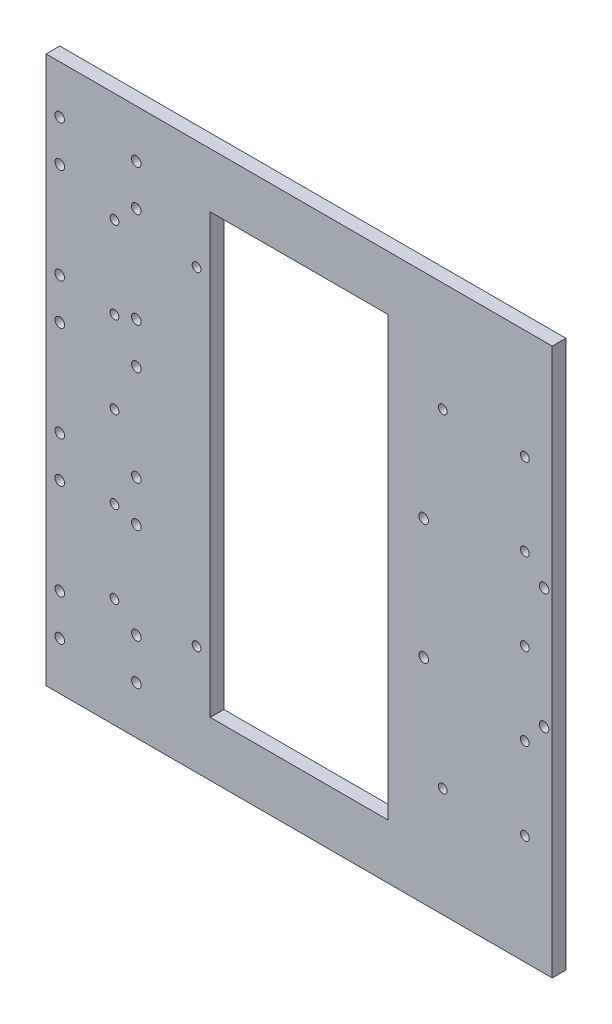
SolidWorks part; units mm, degrees
ref_plane "前视基准面" through (0, 0, 0) normal (0, 0, 1) x (1, 0, 0)
ref_plane "上视基准面" through (0, 0, 0) normal (0, 1, 0) x (1, 0, 0)
ref_plane "右视基准面" through (0, 0, 0) normal (1, 0, 0) x (0, 0, -1)
other "Configuration Table"
sketch "草图1" plane through (0, 0, 0) normal (0, 0, 1) x (1, 0, 0)
  line L1 (0, 0) -> (170, 0)
  line L2 (0, 0) -> (0, 140)
  line L3 (0, 140) -> (170, 140)
  line L4 (170, 0) -> (170, 140)
  dimension "D1" = 170
  dimension "D2" = 140
extrude "凸台-拉伸1" add sketch "草图1" along normal blind 5
sketch "草图3" plane through (0, 0, 5) normal (0, 0, 1) x (1, 0, 0)
  line L0 (160, 130) -> (10, 130)
  line L1 (10, 130) -> (10, 10)
  line L2 (10, 10) -> (160, 10)
  line L3 (160, 10) -> (160, 130)
  line L4 (0, 140) -> (0, 0)
  line L5 (0, 0) -> (170, 0)
  line L6 (170, 0) -> (170, 140)
  line L7 (170, 140) -> (0, 140)
  line L8 (0, 140) -> (0, 0)
  line L9 (0, 0) -> (170, 0)
  line L10 (170, 0) -> (170, 140)
  line L11 (170, 140) -> (0, 140)
  circle A0 centre (10, 130) radius 1.6
  circle A1 centre (160, 130) radius 1.6
  circle A2 centre (10, 10) radius 1.6
  circle A3 centre (160, 10) radius 1.6
  dimension "D3" = 3.2
  dimension "D4" = 3.2
  dimension "D5" = 3.2
  dimension "D6" = 3.2
  dimension "D1" = 0
  dimension "D2" = 10
extrude "切除-拉伸1" cut sketch "草图3" against normal blind 5 contours L0 A0 L1 | L1 A0 L0 | L1 A2 L2 | L2 A2 L1 | L3 A3 L2 | L2 A3 L3 | L0 A1 L3 | L3 A1 L0
sketch "草图4" plane through (0, 0, 5) normal (0, 0, 1) x (1, 0, 0)
  circle A0 centre (10, 130) radius 1.6 construction
  circle A1 centre (10, 130) radius 1.6
  circle A2 centre (40, 130) radius 1.6
  circle A3 centre (70, 130) radius 1.6
  circle A4 centre (100, 130) radius 1.6
  circle A5 centre (130, 130) radius 1.6
  circle A6 centre (160, 130) radius 1.6 construction
  circle A7 centre (10, 10) radius 1.6 construction
  circle A8 centre (10, 10) radius 1.6
  circle A9 centre (40, 10) radius 1.6
  circle A10 centre (70, 10) radius 1.6
  circle A11 centre (100, 10) radius 1.6
  circle A12 centre (130, 10) radius 1.6
  circle A13 centre (160, 10) radius 1.6 construction
  circle A14 centre (160, 130) radius 1.6
  circle A15 centre (10, 100) radius 1.6
  circle A16 centre (160, 100) radius 1.6
  circle A17 centre (10, 70) radius 1.6
  circle A18 centre (160, 70) radius 1.6
  circle A19 centre (10, 40) radius 1.6
  circle A20 centre (160, 40) radius 1.6
  dimension "D2" = 30
  dimension "D3" = 5
  dimension "D6" = 30
  dimension "D4" = 30
  dimension "D1" = 5
  dimension "D5" = 4
extrude "切除-拉伸2" cut sketch "草图4" against normal blind 5
sketch "草图7" plane through (0, 0, 5) normal (0, 0, 1) x (1, 0, 0)
  line L4 (0, 140) -> (0, 0)
  line L5 (0, 0) -> (170, 0)
  line L6 (170, 0) -> (170, 140)
  line L7 (170, 140) -> (0, 140)
  line L8 (0, 140) -> (0, 0)
  line L9 (0, 0) -> (170, 0)
  line L10 (170, 0) -> (170, 140)
  line L11 (170, 140) -> (0, 140)
  circle A1 centre (10, 130) radius 1.6
  circle A2 centre (10, 130) radius 1.6
  circle A3 centre (10, 10) radius 1.6
  circle A4 centre (10, 10) radius 1.6
  circle A5 centre (160, 10) radius 1.6
  circle A6 centre (160, 10) radius 1.6
  circle A7 centre (160, 130) radius 1.6
  circle A8 centre (160, 130) radius 1.6
  circle A9 centre (160, 100) radius 1.6
  circle A10 centre (160, 100) radius 1.6
  circle A11 centre (10, 100) radius 1.6
  circle A12 centre (10, 100) radius 1.6
  circle A13 centre (130, 10) radius 1.6
  circle A14 centre (130, 10) radius 1.6
  circle A15 centre (10, 70) radius 1.6
  circle A16 centre (10, 70) radius 1.6
  circle A17 centre (160, 70) radius 1.6
  circle A18 centre (160, 70) radius 1.6
  circle A19 centre (10, 40) radius 1.6
  circle A20 centre (10, 40) radius 1.6
  circle A21 centre (160, 40) radius 1.6
  circle A22 centre (160, 40) radius 1.6
  circle A23 centre (100, 10) radius 1.6
  circle A24 centre (100, 10) radius 1.6
  circle A25 centre (70, 10) radius 1.6
  circle A26 centre (70, 10) radius 1.6
  circle A27 centre (40, 10) radius 1.6
  circle A28 centre (40, 10) radius 1.6
  circle A29 centre (130, 130) radius 1.6
  circle A30 centre (130, 130) radius 1.6
  circle A31 centre (100, 130) radius 1.6
  circle A32 centre (100, 130) radius 1.6
  circle A33 centre (70, 130) radius 1.6
  circle A34 centre (70, 130) radius 1.6
  circle A35 centre (40, 130) radius 1.6
  circle A36 centre (40, 130) radius 1.6
  dimension "D1" = 0
  dimension "D2" = 0
  dimension "D3" = 0
  dimension "D4" = 0
  dimension "D5" = 0
  dimension "D6" = 0
  dimension "D7" = 0
  dimension "D8" = 0
  dimension "D9" = 0
  dimension "D10" = 0
  dimension "D11" = 0
  dimension "D12" = 0
  dimension "D13" = 0
  dimension "D14" = 0
  dimension "D15" = 0
  dimension "D16" = 0
  dimension "D17" = 0
  dimension "D18" = 0
  dimension "D19" = 0
sketch "草图9" plane through (0, 0, 0) normal (0, -1, 0) x (1, 0, 0)
  line L4 (0, 0) -> (170, 0)
  line L5 (170, 0) -> (170, 5)
  line L6 (170, 5) -> (0, 5)
  line L7 (0, 5) -> (0, 0)
  line L8 (0, 0) -> (170, 0)
  line L9 (170, 0) -> (170, 5)
  line L10 (170, 5) -> (0, 5)
  line L11 (0, 5) -> (0, 0)
  dimension "D1" = 0
extrude "凸台-拉伸2" add sketch "草图9" along normal blind 30
sketch "草图10" plane through (0, 140, 0) normal (0, 1, 0) x (1, 0, 0)
  line L4 (170, 0) -> (0, 0)
  line L5 (0, 0) -> (0, -5)
  line L6 (0, -5) -> (170, -5)
  line L7 (170, -5) -> (170, 0)
  line L8 (170, 0) -> (0, 0)
  line L9 (0, 0) -> (0, -5)
  line L10 (0, -5) -> (170, -5)
  line L11 (170, -5) -> (170, 0)
  dimension "D1" = 0
extrude "凸台-拉伸3" add sketch "草图10" along normal blind 30
sketch "草图8" plane through (0, 0, 5) normal (0, 0, 1) x (1, 0, 0)
  line L1 (45, 150) -> (110, 150)
  line L2 (45, 150) -> (45, -10)
  line L3 (45, -10) -> (110, -10)
  line L4 (0, 170) -> (0, -30)
  line L5 (0, -30) -> (170, -30)
  line L6 (170, -30) -> (170, 170)
  line L7 (0, -30) -> (170, -30)
  line L8 (0, 170) -> (0, -30)
  line L10 (170, -30) -> (170, 170)
  line L12 (110, 150) -> (110, -10)
  line L16 (170, 170) -> (0, 170)
  line L17 (170, 170) -> (0, 170)
  dimension "D2" = 160
  dimension "D3" = 20
  dimension "D4" = 65
  dimension "D5" = 45
  dimension "D1" = 0
extrude "切除-拉伸5" cut sketch "草图8" against normal blind 30 contours L2 L1 L12 L3
sketch "草图6" plane through (0, 0, 5) normal (0, 0, 1) x (1, 0, 0)
  line L1 (120, 95) -> (170, 95) construction
  line L2 (120, 95) -> (120, 45) construction
  line L3 (120, 45) -> (170, 45) construction
  line L4 (170, 95) -> (170, 45) construction
  line L5 (120, 95) -> (170, 45) construction
  line L6 (120, 45) -> (170, 95) construction
  line L9 (0, 170) -> (0, -30) construction
  line L10 (170, -30) -> (0, -30) construction
  circle A1 centre (123, 92) radius 1.75
  circle A2 centre (167, 92) radius 1.75
  circle A3 centre (123, 48) radius 1.75
  circle A4 centre (167, 48) radius 1.75
  point P0 (145, 70)
  dimension "D5" = 3.5
  dimension "D6" = 3
  dimension "D7" = 3.5
  dimension "D8" = 3
  dimension "D9" = 3
  dimension "D10" = 3.5
  dimension "D11" = 3.5
  dimension "D12" = 3
  dimension "D1" = 50
  dimension "D2" = 50
  dimension "D3" = 75
  dimension "D4" = 120
extrude "切除-拉伸6" cut sketch "草图6" against normal blind 30
sketch "草图13" plane through (0, 0, 0) normal (-1, 0, 0) x (0, 0, 1)
  line L4 (0, 170) -> (0, -30)
  line L5 (0, -30) -> (5, -30)
  line L6 (5, -30) -> (5, 170)
  line L7 (5, 170) -> (0, 170)
  line L8 (0, 170) -> (0, -30)
  line L9 (0, -30) -> (5, -30)
  line L10 (5, -30) -> (5, 170)
  line L11 (5, 170) -> (0, 170)
  dimension "D1" = 0
extrude "凸台-拉伸4" add sketch "草图13" along normal blind 15
sketch "草图14" plane through (0, 0, 5) normal (0, 0, 1) x (1, 0, 0)
  line L1 (-10, 137.5) -> (18, 137.5)
  line L2 (-10, 137.5) -> (-10, 152.5)
  line L3 (-10, 152.5) -> (18, 152.5)
  line L4 (170, 170) -> (-15, 170)
  line L5 (-15, 170) -> (-15, -30)
  line L6 (-15, -30) -> (170, -30)
  line L7 (170, -30) -> (170, 170)
  line L8 (170, 170) -> (-15, 170)
  line L9 (-15, 170) -> (-15, -30)
  line L10 (-15, -30) -> (170, -30)
  line L11 (170, -30) -> (170, 170)
  line L12 (18, 137.5) -> (18, 152.5)
  line L13 (-10, 137.5) -> (18, 152.5) construction
  line L14 (-10, 152.5) -> (18, 137.5) construction
  circle A0 centre (-10, 152.5) radius 1.75
  circle A1 centre (18, 152.5) radius 1.75
  circle A2 centre (18, 137.5) radius 1.75
  circle A3 centre (-10, 137.5) radius 1.75
  circle A4 centre (-10, 102.5) radius 1.75
  circle A5 centre (-10, 87.5) radius 1.75
  circle A6 centre (18, 87.5) radius 1.75
  circle A7 centre (18, 102.5) radius 1.75
  circle A8 centre (-10, 52.5) radius 1.75
  circle A9 centre (-10, 37.5) radius 1.75
  circle A10 centre (18, 37.5) radius 1.75
  circle A11 centre (18, 52.5) radius 1.75
  circle A12 centre (-10, 2.5) radius 1.75
  circle A13 centre (-10, -12.5) radius 1.75
  circle A14 centre (18, -12.5) radius 1.75
  circle A15 centre (18, 2.5) radius 1.75
  point P2 (4, 145)
  dimension "D6" = 3.5
  dimension "D7" = 3.5
  dimension "D8" = 3.5
  dimension "D9" = 3.5
  dimension "D2" = 28
  dimension "D3" = 15
  dimension "D4" = 17.5
  dimension "D5" = 5
  dimension "D11" = 35
  dimension "D1" = 0
  dimension "D10" = 4
extrude "切除-拉伸7" cut sketch "草图14" against normal blind 15 contours L3 A0 L2 | L2 A0 L3 | L1 A3 L2 | L2 A3 L1 | L12 A2 L1 | L1 A2 L12 | L3 A1 L12 | L12 A1 L3 | A4 | A7 | A5 | A6 | A8 | A11 | A9 | A10 | A12 | A15 | A13 | A14
